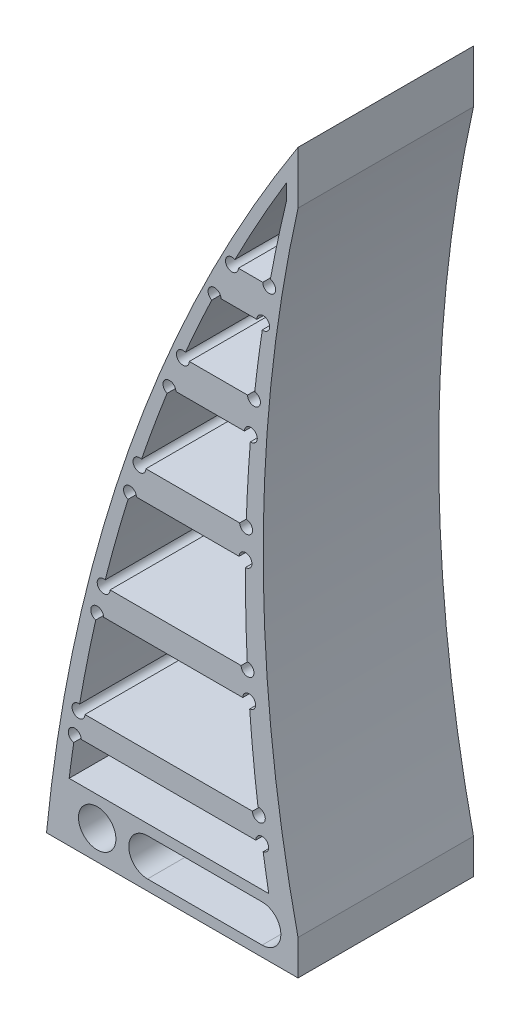
SolidWorks part; units mm, degrees
ref_plane "Plan de face" through (0, 0, 0) normal (0, 0, 1) x (1, 0, 0)
ref_plane "Plan de dessus" through (0, 0, 0) normal (0, 1, 0) x (1, 0, 0)
ref_plane "Plan de droite" through (0, 0, 0) normal (1, 0, 0) x (0, 0, -1)
ref_plane "Plan1" through (0, 0, 15) normal (0, 0, 1) x (1, 0, 0)
sketch "Esquisse1" plane through (0, 0, 15) normal (0, 0, 1) x (1, 0, 0)
  line L0 (-4.3127, 41) -> (-9.2951, 41)
  line L1 (-6.5867, 47) -> (-3.5209, 47)
  line L2 (-10.4428, 38.2) -> (-4.5831, 38.2)
  line L3 (-4.9864, 31.2) -> (-13.0045, 31.2)
  line L4 (-3.0151, 50) -> (-5.0996, 50)
  line L5 (-1, 58.3658) -> (-1, 56.9728)
  line L6 (-3.8989, 10.4) -> (-18.215, 10.4)
  line L7 (-16.6185, 18.4) -> (-4.7235, 18.4)
  line L8 (-13.8166, 28.7) -> (-5.0366, 28.7)
  line L9 (-4.8661, 20.7) -> (-16.067, 20.7)
  line L10 (-18.5375, 8.4) -> (-3.6123, 8.4)
  line L11 (-2.5, 5) -> (-19.5666, 5)
  line L12 (0, 57) -> (0, 61.5)
  line L13 (-21.5, 0) -> (0, 0)
  line L14 (0, 0) -> (0, 3)
  line L15 (-3.0684, 0.9) -> (-12.8684, 0.9)
  line L16 (-12.8684, 4.1) -> (-3.0684, 4.1)
  arc A0 (-3.7026, 41.5467) -> (-4.3127, 41) centre (-3.7627, 41) cw
  arc A1 (-9.2951, 41) -> (-9.6299, 41.5061) centre (-9.8451, 41) cw
  arc A2 (-9.6299, 41.5061) -> (-7.374, 46.5038) centre (116.5567, -12.4462) cw
  arc A3 (-7.374, 46.5038) -> (-6.5867, 47) centre (-7.1367, 47) cw
  arc A4 (-3.5209, 47) -> (-3.0547, 46.4564) centre (-2.9709, 47) cw
  arc A5 (-3.0547, 46.4564) -> (-3.7026, 41.5467) centre (122.4045, 27.4031) ccw
  arc A6 (-11.1948, 37.6884) -> (-10.4428, 38.2) centre (-10.9928, 38.2) cw
  arc A7 (-4.5831, 38.2) -> (-4.0787, 37.6519) centre (-4.0331, 38.2) cw
  arc A8 (-4.0787, 37.6519) -> (-4.4188, 31.7497) centre (122.4045, 27.4031) ccw
  arc A9 (-4.4188, 31.7497) -> (-4.9864, 31.2) centre (-4.4364, 31.2) cw
  arc A10 (-13.0045, 31.2) -> (-13.3785, 31.7211) centre (-13.5545, 31.2) cw
  arc A11 (-13.3785, 31.7211) -> (-11.1948, 37.6884) centre (116.5567, -12.4462) cw
  arc A12 (-2.366, 50.541) -> (-3.0151, 50) centre (-2.4651, 50) cw
  arc A13 (-5.0996, 50) -> (-5.3984, 50.4893) centre (-5.6496, 50) cw
  arc A14 (-5.3984, 50.4893) -> (-1, 58.3658) centre (116.5567, -12.4462) cw
  arc A15 (-1, 56.9728) -> (-2.366, 50.541) centre (122.4045, 27.4031) ccw
  arc A16 (-3.4215, 10.9452) -> (-3.8989, 10.4) centre (-3.3489, 10.4) cw
  arc A17 (-18.215, 10.4) -> (-18.6724, 10.9421) centre (-18.765, 10.4) cw
  arc A18 (-18.6724, 10.9421) -> (-17.291, 17.8638) centre (116.5567, -12.4462) cw
  arc A19 (-17.291, 17.8638) -> (-16.6185, 18.4) centre (-17.1685, 18.4) cw
  arc A20 (-4.7235, 18.4) -> (-4.1332, 17.8515) centre (-4.1735, 18.4) cw
  arc A21 (-4.1332, 17.8515) -> (-3.4215, 10.9452) centre (122.4045, 27.4031) ccw
  arc A22 (-16.067, 20.7) -> (-16.4831, 21.2334) centre (-16.617, 20.7) cw
  arc A23 (-16.4831, 21.2334) -> (-14.5304, 28.175) centre (116.5567, -12.4462) cw
  arc A24 (-14.5304, 28.175) -> (-13.8166, 28.7) centre (-14.3666, 28.7) cw
  arc A25 (-5.0366, 28.7) -> (-4.491, 28.15) centre (-4.4866, 28.7) cw
  arc A26 (-4.491, 28.15) -> (-4.3439, 21.2493) centre (122.4045, 27.4031) ccw
  arc A27 (-4.3439, 21.2493) -> (-4.8661, 20.7) centre (-4.3161, 20.7) cw
  arc A28 (-19.17, 7.8562) -> (-18.5375, 8.4) centre (-19.0875, 8.4) cw
  arc A29 (-3.6123, 8.4) -> (-2.9787, 7.8564) centre (-3.0623, 8.4) cw
  arc A30 (-2.9787, 7.8564) -> (-2.5, 5) centre (122.4045, 27.4031) ccw
  arc A31 (-19.5666, 5) -> (-19.17, 7.8562) centre (116.5567, -12.4462) cw
  arc A32 (0, 3) -> (0, 57) centre (120.9383, 30) cw
  arc A33 (0, 61.5) -> (-21.5, 0) centre (116.308, -13.6686) ccw
  arc A34 (-3.0684, 4.1) -> (-3.0684, 0.9) centre (-3.0684, 2.5) cw
  arc A35 (-12.8684, 0.9) -> (-12.8684, 4.1) centre (-12.8684, 2.5) cw
  circle A36 centre (-17.1685, 2.5) radius 1.6
extrude "Boss.-Extru.1" add sketch "Esquisse1" against normal blind 15
